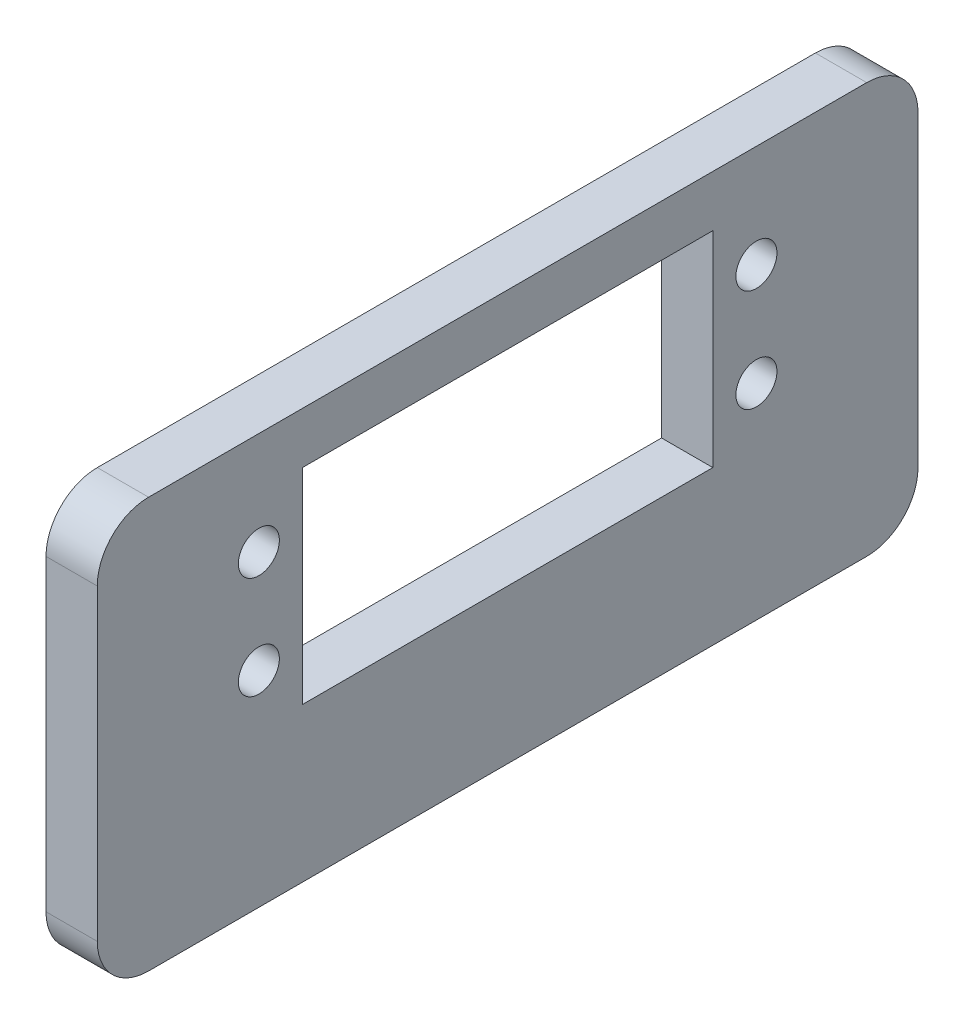
SolidWorks part; units mm, degrees
ref_plane "Front Plane" through (0, 0, 0) normal (0, 0, 1) x (1, 0, 0)
ref_plane "Top Plane" through (0, 0, 0) normal (0, 1, 0) x (1, 0, 0)
ref_plane "Right Plane" through (0, 0, 0) normal (1, 0, 0) x (0, 0, -1)
sketch "Sketch1" plane through (0, 0, 0) normal (1, 0, 0) x (0, 0, -1)
  line L0 (0, 24.3772) -> (0, -25.8719) construction
  line L1 (40, -20) -> (-40, -20)
  line L2 (40, -20) -> (40, 20)
  line L3 (40, 20) -> (-40, 20)
  line L4 (-40, -20) -> (-40, 20)
  line L5 (40, -20) -> (-40, 20) construction
  line L6 (40, 20) -> (-40, -20) construction
  line L7 (-37.2242, 0) -> (45.1246, 0) construction
  line L9 (-40, 5) -> (40, 5) construction
  line L12 (20, -5) -> (-20, -5)
  line L13 (20, -5) -> (20, 15)
  line L14 (20, 15) -> (-20, 15)
  line L15 (-20, -5) -> (-20, 15)
  line L16 (20, -5) -> (-20, 15) construction
  line L17 (20, 15) -> (-20, -5) construction
  circle A2 centre (24.25, 10) radius 2
  circle A3 centre (24.25, 0) radius 2
  circle A7 centre (-24.25, 10) radius 2
  circle A8 centre (-24.25, 0) radius 2
  point P0 (0, 0)
  point P30 (0, 5)
  dimension "D2" = 5
  dimension "D3" = 4
  dimension "D1" = 15
  dimension "D4" = 40
  dimension "D5" = 80
  dimension "D7" = 48.5
  dimension "D11" = 40
  dimension "D12" = 20
extrude "Boss-Extrude1" add sketch "Sketch1" along normal blind 5
fillet "Fillet1" radius 5 4 edges at (2.5, -20, 40) (2.5, -20, -40) (2.5, 20, -40) (2.5, 20, 40)
